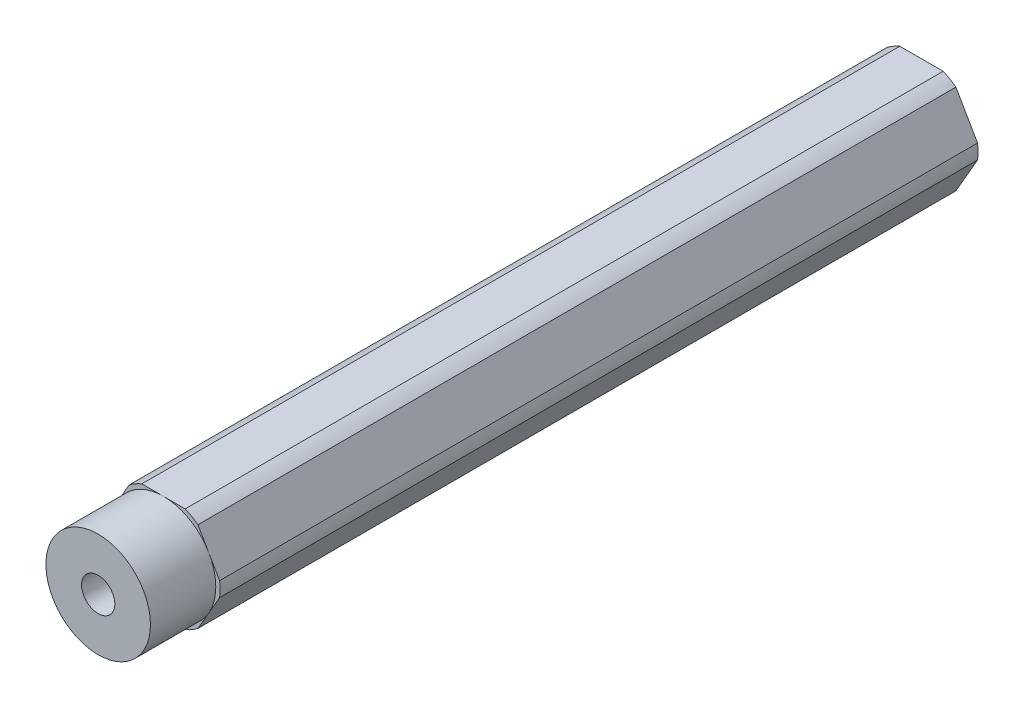
SolidWorks part; units mm, degrees
material "7075-T6 (SN)"
ref_plane "Front Plane" through (0, 0, 0) normal (0, 0, 1) x (1, 0, 0)
ref_plane "Top Plane" through (0, 0, 0) normal (0, 1, 0) x (1, 0, 0)
ref_plane "Right Plane" through (0, 0, 0) normal (1, 0, 0) x (0, 0, -1)
sketch "Sketch1" plane through (0, 0, 0) normal (0, 0, 1) x (1, 0, 0)
  line L1 (3.6662, 6.35) -> (-3.6662, 6.35)
  line L2 (-3.6662, 6.35) -> (-7.3323, 0)
  line L3 (-7.3323, 0) -> (-3.6662, -6.35)
  line L4 (-3.6662, -6.35) -> (3.6662, -6.35)
  line L5 (3.6662, -6.35) -> (7.3323, 0)
  line L6 (7.3323, 0) -> (3.6662, 6.35)
  circle A0 centre (0, 0) radius 6.35 construction
  circle A1 centre (0, 0) radius 6.875
  circle A2 centre (0, 0) radius 2.0193
  point P10 (0, 6.35)
  dimension "D1" = 13.75
  dimension "D2" = 12.7
  dimension "D3" = 4.0386
extrude "Boss-Extrude1" add sketch "Sketch1" along normal mid plane 100.0125 contours L6 A1 L1 L2 L3 L4 L5
sketch "Sketch2" plane through (0, 0, 50.0062) normal (0, 0, 1) x (1, 0, 0)
  circle A0 centre (0, 0) radius 6.35
  dimension "D1" = 12.7
extrude "Cut-Extrude2" cut sketch "Sketch2" against normal blind 7.9375 flip side to cut
equation "\"D1@Sketch1\"=13.75mm"
